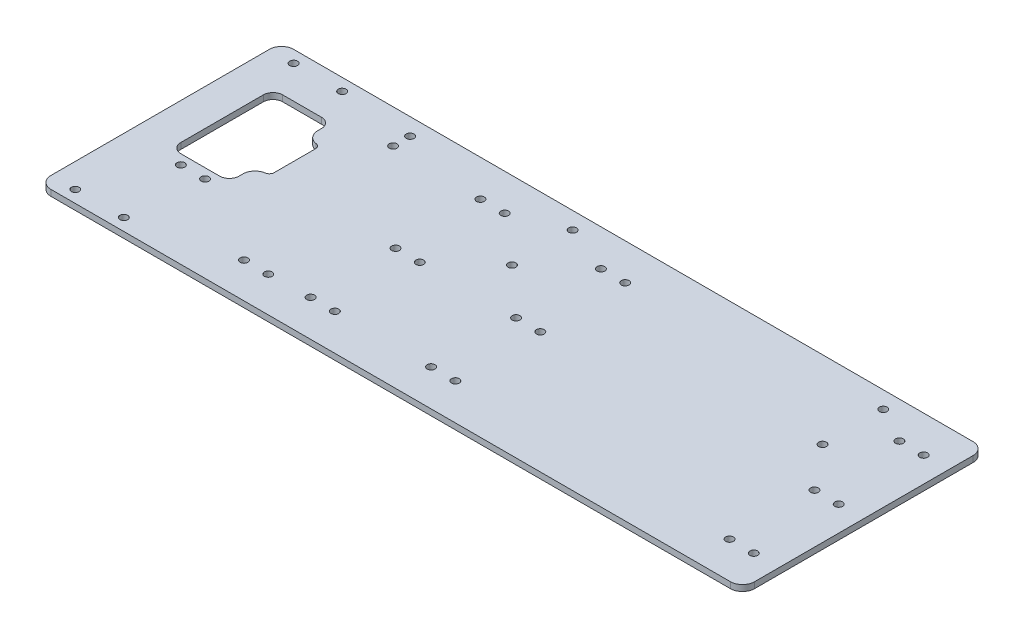
SolidWorks part; units mm, degrees
ref_plane "Front Plane" through (0, 0, 0) normal (0, 0, 1) x (1, 0, 0)
ref_plane "Top Plane" through (0, 0, 0) normal (0, 1, 0) x (1, 0, 0)
ref_plane "Right Plane" through (0, 0, 0) normal (1, 0, 0) x (0, 0, -1)
sketch "Sketch1" plane through (0, 0, 0) normal (0, 1, 0) x (1, 0, 0)
  line L0 (171.0189, 63.5) -> (171.0189, 44.45) construction
  line L1 (184.15, 63.5) -> (-184.15, 63.5)
  line L2 (184.15, 63.5) -> (184.15, -63.5)
  line L3 (184.15, -63.5) -> (-184.15, -63.5)
  line L4 (-184.15, 63.5) -> (-184.15, -63.5)
  line L5 (184.15, 63.5) -> (-184.15, -63.5) construction
  line L6 (184.15, -63.5) -> (-184.15, 63.5) construction
  line L7 (-128.2684, -0.635) -> (-128.2684, 31.115) construction
  line L8 (-128.2684, 31.115) -> (-134.6184, 31.115) construction
  line L9 (-128.2684, 5.715) -> (-134.6184, 5.715) construction
  line L12 (-165.0984, -13.335) -> (-165.0984, 40.005)
  line L15 (-134.6184, -13.335) -> (-165.0984, -13.335)
  line L17 (-134.6184, 40.005) -> (-165.0984, 40.005)
  line L18 (0, 63.5) -> (0, -63.5) construction
  line L19 (-134.6184, 40.005) -> (-134.6184, -13.335)
  line L20 (171.0189, 44.45) -> (184.15, 44.45) construction
  line L21 (0, 0) -> (-126.9984, 0) construction
  line L22 (-82.55, -45.0215) -> (-95.25, -45.0215) construction
  line L23 (171.0189, 44.45) -> (171.0189, 0) construction
  line L25 (171.0189, 0) -> (171.0189, -44.45) construction
  line L26 (171.0189, 44.45) -> (158.3189, 44.45) construction
  line L30 (171.0189, 0) -> (158.3189, 0) construction
  line L31 (171.0189, -44.45) -> (158.3189, -44.45) construction
  line L32 (158.3189, 44.45) -> (14.8089, 44.45) construction
  line L33 (14.8089, 44.45) -> (14.8089, 0) construction
  line L34 (14.8089, 0) -> (14.8089, -44.45) construction
  line L35 (-146.05, -57.15) -> (-184.15, -57.15) construction
  line L36 (-146.05, 57.15) -> (-184.15, 57.15) construction
  line L37 (-128.2684, -0.635) -> (-128.2684, 5.715) construction
  line L38 (-184.15, -18.415) -> (-154.94, -18.415) construction
  line L39 (-154.94, -18.415) -> (-142.24, -18.415) construction
  line L40 (-134.6184, 26.67) -> (-126.9984, 26.67)
  line L41 (-126.9984, 26.67) -> (-126.9984, 0)
  line L42 (-126.9984, 0) -> (-134.6184, 0)
  line L43 (14.8089, 44.45) -> (2.1089, 44.45) construction
  line L44 (14.8089, 0) -> (2.1089, 0) construction
  line L45 (14.8089, -44.45) -> (2.1089, -44.45) construction
  line L46 (2.1089, 44.45) -> (-48.2678, 44.45) construction
  line L47 (-48.2678, 44.45) -> (-60.9678, 44.45) construction
  line L48 (-48.2678, 44.45) -> (-48.2678, 0) construction
  line L49 (-48.2678, 0) -> (-60.9678, 0) construction
  line L50 (-48.2678, 0) -> (-48.2678, -44.45) construction
  line L51 (-48.2678, -44.45) -> (-60.9678, -44.45) construction
  circle A12 centre (-146.05, -57.15) radius 2.032
  circle A13 centre (-171.45, -57.15) radius 2.032
  circle A14 centre (-146.05, 57.15) radius 2.032
  circle A15 centre (-171.45, 57.15) radius 2.032
  circle A18 centre (-154.94, -18.415) radius 2.032
  circle A19 centre (-142.24, -18.415) radius 2.032
  circle A20 centre (-95.25, -45.0215) radius 2.032
  circle A21 centre (-82.55, -45.0215) radius 2.032
  circle A24 centre (171.0189, 44.45) radius 2.032
  circle A25 centre (171.0189, 0) radius 2.032
  circle A26 centre (171.0189, -44.45) radius 2.032
  circle A27 centre (158.3189, 44.45) radius 2.032
  circle A28 centre (158.3189, 0) radius 2.032
  circle A29 centre (158.3189, -44.45) radius 2.032
  circle A30 centre (2.1089, 44.45) radius 2.032
  circle A31 centre (2.1089, 0) radius 2.032
  circle A32 centre (2.1089, -44.45) radius 2.032
  circle A33 centre (14.8089, -44.45) radius 2.032
  circle A34 centre (14.8089, 0) radius 2.032
  circle A35 centre (14.8089, 44.45) radius 2.032
  circle A36 centre (-60.9678, 44.45) radius 2.032
  circle A37 centre (-48.2678, 44.45) radius 2.032
  circle A38 centre (-60.9678, 0) radius 2.032
  circle A39 centre (-60.9678, -44.45) radius 2.032
  circle A40 centre (-48.2678, -44.45) radius 2.032
  circle A41 centre (-48.2678, 0) radius 2.032
  point P0 (0, 0)
  point P11 (-128.2684, -0.635)
  point P13 (-134.6184, 31.115)
  point P17 (-134.6184, 5.715)
  point P37 (0, 0)
  dimension "D5" = 13.335
  dimension "D6" = 29.21
  dimension "D18" = 12.7
  dimension "D13" = 4.064
  dimension "D23" = 44.45
  dimension "D24" = 44.45
  dimension "D31" = 12.7
  dimension "D32" = 143.51
  dimension "D35" = 50.3767
  dimension "D1" = 368.3
  dimension "D2" = 127
  dimension "D3" = 128.27
  dimension "D4" = 25.4
  dimension "D7" = 6.35
  dimension "D8" = 30.48
  dimension "D9" = 53.34
  dimension "D10" = 8.89
  dimension "D11" = 19.05
  dimension "D12" = 12.7
  dimension "D14" = 38.1
  dimension "D15" = 6.35
  dimension "D16" = 12.7
  dimension "D17" = 6.35
  dimension "D19" = 31.75
  dimension "D20" = 19.05
  dimension "D21" = 13.1311
  dimension "D22" = 5.08
  dimension "D25" = 88.9
  dimension "D26" = 12.7
  dimension "D27" = 7.62
  dimension "D28" = 26.67
  dimension "D29" = 13.335
  dimension "D30" = 18.4785
  dimension "D33" = 44.45
  dimension "D34" = 44.45
extrude "Boss-Extrude1" add sketch "Sketch1" along normal blind 3.175
fillet "Fillet1" radius 5.08 4 edges at (-134.6184, 1.5875, 13.335) (-165.0984, 1.5875, 13.335) (-165.0984, 1.5875, -40.005) (-134.6184, 1.5875, -40.005)
fillet "Fillet3" radius 6.35 4 edges at (184.15, 1.5875, 63.5) (184.15, 1.5875, -63.5) (-184.15, 1.5875, 63.5) (-184.15, 1.5875, -63.5)
fillet "Fillet4" radius 2.54 2 edges at (-126.9984, 1.5875, 0) (-126.9984, 1.5875, -26.67)
fillet "Fillet5" radius 6.35 2 edges at (-134.6184, 1.5875, 0) (-134.6184, 1.5875, -26.67)
sketch "Sketch2" plane through (0, 3.175, 0) normal (0, 1, 0) x (1, 0, 0)
  line L0 (-22.86, 54.61) -> (184.15, 54.61) construction
  line L2 (184.15, 57.15) -> (184.15, -57.15) construction
  line L3 (-22.86, 54.61) -> (-22.86, 22.86) construction
  line L4 (139.7, 54.61) -> (139.7, 22.86)
  line L5 (177.8, 63.5) -> (-177.8, 63.5) construction
  line L6 (-22.86, 54.61) -> (-107.95, 54.61) construction
  line L7 (-107.95, 54.61) -> (-107.95, 45.72) construction
  circle A0 centre (-22.86, 54.61) radius 2.032
  circle A1 centre (-22.86, 22.86) radius 2.032
  circle A2 centre (139.7, 54.61) radius 2.032
  circle A3 centre (139.7, 22.86) radius 2.032
  circle A4 centre (-107.95, 54.61) radius 2.032
  circle A5 centre (-107.95, 45.72) radius 2.032
  dimension "D5" = 4.064
  dimension "D6" = 8.89
  dimension "D1" = 207.01
  dimension "D2" = 31.75
  dimension "D3" = 44.45
  dimension "D4" = 8.89
  dimension "D7" = 292.1
extrude "Cut-Extrude1" cut sketch "Sketch2" against normal up to next
equation "\".80.55in\"=0.55"
